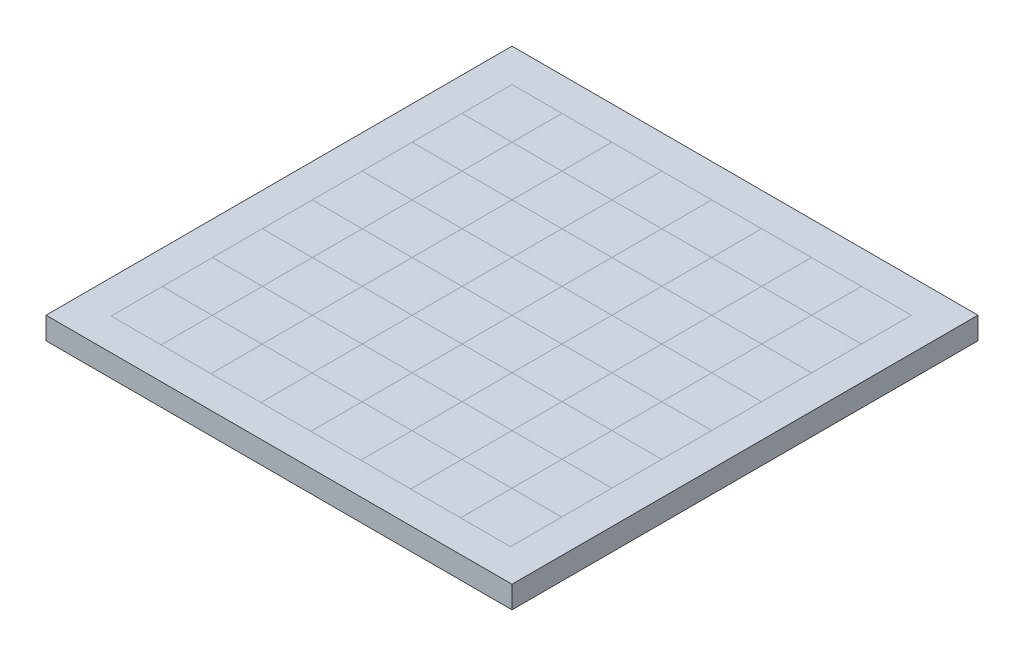
SolidWorks part; units mm, degrees
ref_plane "Front Plane" through (0, 0, 0) normal (0, 0, 1) x (1, 0, 0)
ref_plane "Top Plane" through (0, 0, 0) normal (0, 1, 0) x (1, 0, 0)
ref_plane "Right Plane" through (0, 0, 0) normal (1, 0, 0) x (0, 0, -1)
sketch "Sketch1" plane through (0, 0, 0) normal (0, 1, 0) x (1, 0, 0)
  line L1 (0, 0) -> (533.4, 0)
  line L2 (0, 0) -> (0, 533.4)
  line L3 (0, 533.4) -> (533.4, 533.4)
  line L4 (533.4, 0) -> (533.4, 533.4)
  dimension "D1" = 533.4
  dimension "D2" = 533.4
extrude "Boss-Extrude1" add sketch "Sketch1" along normal blind 25.4
sketch "Sketch3" plane through (0, 25.4, 0) normal (0, 1, 0) x (1, 0, 0)
  line L258 (381, 495.3) -> (381, 36.4067)
  line L259 (38.1, 438.15) -> (495.3, 438.15)
  line L261 (533.4, 533.4) -> (0, 533.4) construction
  line L262 (38.1, 495.3) -> (495.3, 495.3)
  line L263 (38.1, 495.3) -> (38.1, 36.4067)
  line L264 (38.1, 36.4067) -> (495.3, 36.4067)
  line L265 (495.3, 495.3) -> (495.3, 36.4067)
  line L266 (0, 533.4) -> (0, 0) construction
  line L267 (95.25, 495.3) -> (95.25, 36.4067)
  line L268 (152.4, 495.3) -> (152.4, 36.4067)
  line L269 (209.55, 495.3) -> (209.55, 36.4067)
  line L270 (266.7, 495.3) -> (266.7, 36.4067)
  line L271 (323.85, 495.3) -> (323.85, 36.4067)
  line L272 (38.1, 381) -> (495.3, 381)
  line L273 (438.15, 495.3) -> (438.15, 36.4067)
  line L274 (38.1, 323.85) -> (495.3, 323.85)
  line L275 (38.1, 266.7) -> (495.3, 266.7)
  line L276 (38.1, 209.55) -> (495.3, 209.55)
  line L277 (38.1, 152.4) -> (495.3, 152.4)
  line L278 (38.1, 95.0071) -> (495.3, 95.0071)
  dimension "D1" = 38.1
  dimension "D2" = 458.8933
  dimension "D5" = 57.15
  dimension "D6" = 57.15
  dimension "D3" = 38.1
  dimension "D4" = 457.2
  dimension "D7" = 57.15
  dimension "D8" = 57.15
  dimension "D9" = 57.15
  dimension "D10" = 57.15
  dimension "D11" = 57.15
  dimension "D12" = 57.15
  dimension "D13" = 57.15
  dimension "D14" = 57.15
  dimension "D15" = 57.15
  dimension "D16" = 57.15
  dimension "D17" = 57.15
  dimension "D18" = 57.3929
split line "Split Line3"
